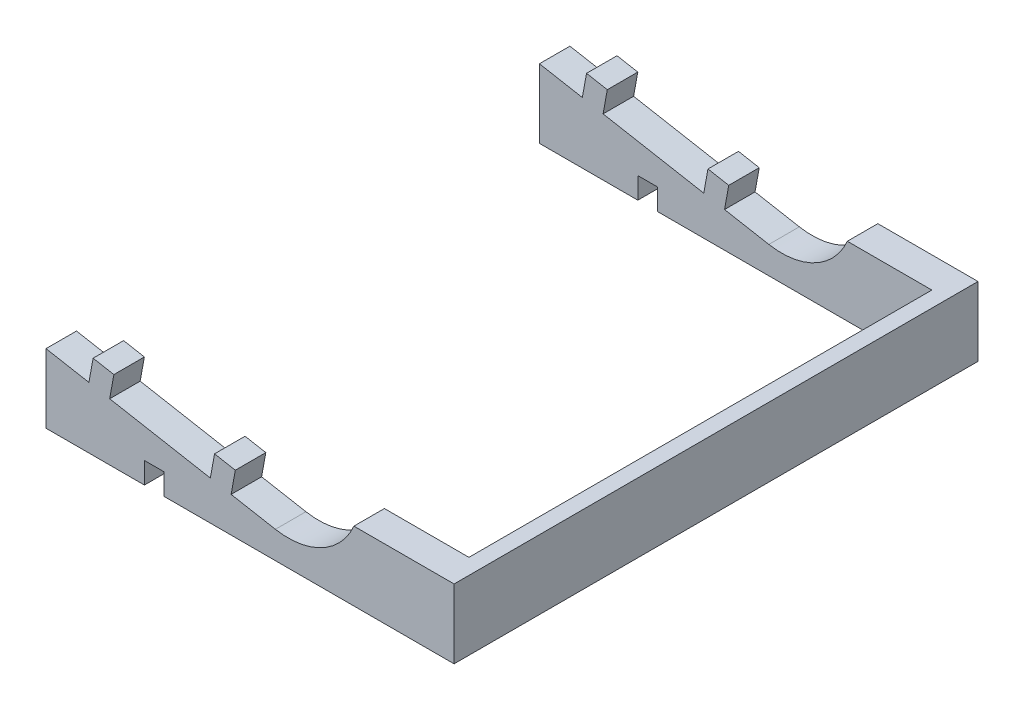
SolidWorks part; units mm, degrees
ref_plane "Front Plane" through (0, 0, 0) normal (0, 0, 1) x (1, 0, 0)
ref_plane "Top Plane" through (0, 0, 0) normal (0, 1, 0) x (1, 0, 0)
ref_plane "Right Plane" through (0, 0, 0) normal (1, 0, 0) x (0, 0, -1)
sketch "Sketch1" plane through (0, 0, 0) normal (0, 0, 1) x (1, 0, 0)
  line L1 (-34.231, 10.5591) -> (-34.7683, 7.6076) construction
  line L8 (-37.7198, 8.1449) -> (-37.1825, 11.0964) construction
  line L9 (-37.1825, 11.0964) -> (-34.231, 10.5591) construction
  line L10 (-18.7014, 7.7323) -> (-19.2386, 4.7808) construction
  line L12 (-22.1901, 5.3181) -> (-21.6529, 8.2696) construction
  line L13 (-21.6529, 8.2696) -> (-18.7014, 7.7323) construction
  line L14 (-34.231, 10.5591) -> (-34.7683, 7.6076) construction
  line L15 (-13.748, 3.629) -> (-19.4131, 4.6601)
  line L27 (-37.7198, 8.1449) -> (-37.1825, 11.0964) construction
  line L28 (-37.1825, 11.0964) -> (-34.231, 10.5591) construction
  line L29 (-18.7014, 7.7323) -> (-19.2386, 4.7808) construction
  line L30 (-18.8758, 7.6116) -> (-19.4131, 4.6601)
  line L31 (-22.1901, 5.3181) -> (-21.6529, 8.2696) construction
  line L32 (-21.6529, 8.2696) -> (-18.7014, 7.7323) construction
  line L33 (-13.7212, 3.7765) -> (-19.2386, 4.7808) construction
  line L34 (-13.7212, 3.7765) -> (-19.2386, 4.7808) construction
  line L35 (-22.1901, 5.3181) -> (-34.7683, 7.6076) construction
  line L36 (-22.1901, 5.3181) -> (-34.7683, 7.6076) construction
  line L37 (-37.7198, 8.1449) -> (-43.2362, 9.149) construction
  line L39 (-37.7198, 8.1449) -> (-43.2362, 9.149) construction
  line L41 (-3.8103, 9.149) -> (9.25, 9.149) construction
  line L42 (9.25, 35.1605) -> (9.25, -1.5) construction
  line L43 (-43.2362, 9.149) -> (-43.2362, 0) construction
  line L45 (-53.75, 0) -> (-30.5, 0) construction
  line L46 (-43.2362, 0) -> (9.25, 0) construction
  line L47 (9.25, 0) -> (9.25, 9.149) construction
  line L48 (-21.5322, 8.0952) -> (-18.8758, 7.6116)
  line L49 (-22.0694, 5.1437) -> (-21.5322, 8.0952)
  line L50 (-22.0694, 5.1437) -> (-34.9427, 7.4869)
  line L51 (-34.4055, 10.4384) -> (-34.9427, 7.4869)
  line L52 (-37.0618, 10.9219) -> (-34.4055, 10.4384)
  line L53 (-37.5991, 7.9704) -> (-37.0618, 10.9219)
  line L54 (-37.5991, 7.9704) -> (-43.0862, 8.9692)
  line L55 (-43.0862, 8.9692) -> (-43.0862, 0.15)
  line L56 (-43.0862, 0.15) -> (9.1, 0.15)
  line L57 (9.1, 0.15) -> (9.1, 8.999)
  line L58 (-3.7111, 8.999) -> (9.1, 8.999)
  arc A1 (-13.7212, 3.7765) -> (-3.6353, 15.6625) centre (-12.1094, 12.631) ccw construction
  arc A3 (-13.7212, 3.7765) -> (-3.8103, 9.149) centre (-12.1094, 12.631) ccw construction
  arc A4 (-13.748, 3.629) -> (-3.7111, 8.999) centre (-12.1094, 12.631) ccw
  dimension "D1" = 0.15
extrude "Boss-Extrude1" add sketch "Sketch1" along normal up to surface (67 mm away)
sketch "Sketch2" plane through (-43.0862, 0, 0) normal (-1, 0, 0) x (0, 0, 1)
  line L2 (67, 0.15) -> (0, 0.15) construction
  line L3 (3.9, 17.848) -> (63.1, 17.848)
  line L4 (3.9, 17.848) -> (3.9, 0.15)
  line L5 (3.9, 0.15) -> (63.1, 0.15)
  line L6 (63.1, 17.848) -> (63.1, 0.15)
  line L7 (3.9, 17.848) -> (63.1, 0.15) construction
  line L8 (67, 8.999) -> (0, 8.999) construction
  line L9 (3.9, 0.15) -> (63.1, 17.848) construction
  line L10 (3.9, 11.0964) -> (3.9, 8.1449) construction
  line L11 (3.9, 11.0964) -> (3.9, 8.1449) construction
  point P0 (0, 0)
  point P1 (33.5, 8.999)
  point P8 (33.5, 0.15)
  point P11 (3.9, 8.999)
  line M16 (67, 8.9692) -> (0, 8.9692)
  line M18 (0, 0.15) -> (67, 0.15)
extrude "Cut-Extrude1" cut sketch "Sketch2" against normal offset from surface (50.1862 mm away) 2 contours L6 L4 M16 M18
sketch "Sketch3" plane through (0, 0, 0) normal (0, 0, -1) x (-1, 0, 0)
  line L0 (28, 5.75) -> (28, 0) construction
  line L1 (28, 2.875) -> (30.5, 2.875)
  line L2 (28, 2.875) -> (28, 0)
  line L3 (28, 0) -> (30.5, 0)
  line L4 (30.5, 2.875) -> (30.5, 0)
  line L5 (30.5, 5.75) -> (30.5, 0) construction
  line L7 (30.5, 5.75) -> (30.5, 0) construction
  point P7 (0, 0)
  point P10 (0, 0)
  point P11 (30.5, 2.875)
extrude "Cut-Extrude2" cut sketch "Sketch3" against normal through all
